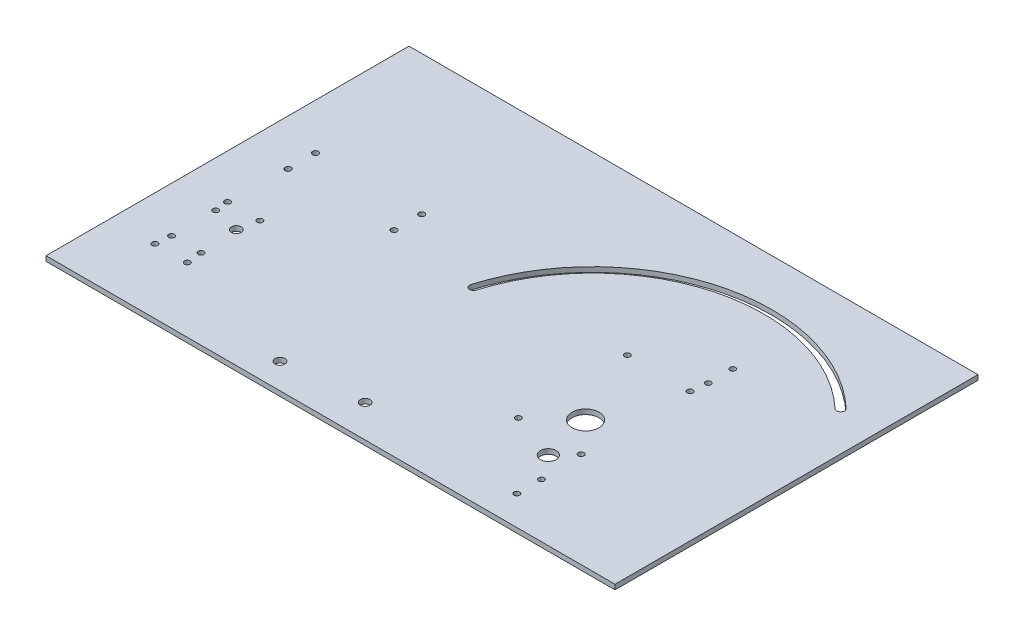
SolidWorks part; units mm, degrees
ref_plane "Front Plane" through (0, 0, 0) normal (0, 0, 1) x (1, 0, 0)
ref_plane "Top Plane" through (0, 0, 0) normal (0, 1, 0) x (1, 0, 0)
ref_plane "Right Plane" through (0, 0, 0) normal (1, 0, 0) x (0, 0, -1)
sketch "Sketch1" plane through (0, 0, 0) normal (0, 1, 0) x (1, 0, 0)
  line L1 (-158.75, 88.9) -> (158.75, 88.9)
  line L2 (-158.75, 88.9) -> (-158.75, -88.9)
  line L3 (-158.75, -88.9) -> (158.75, -88.9)
  line L4 (158.75, 88.9) -> (158.75, -88.9)
  line L5 (-158.75, 88.9) -> (158.75, -88.9) construction
  line L6 (-158.75, -88.9) -> (158.75, 88.9) construction
  circle A0 centre (-111.76, -12.7) radius 3.175
  circle A1 centre (107.95, -6.35) radius 8.7313
  circle A4 centre (-129.032, 55.88) radius 1.905
  circle A5 centre (-60.452, 55.88) radius 1.905
  circle A7 centre (-129.032, 38.1) radius 1.905
  circle A8 centre (-60.452, 38.1) radius 1.905
  point P0 (0, 0)
  dimension "D3" = 6.35
  dimension "D4" = 17.4625
  dimension "D14" = 3.81
  dimension "D17" = 17.78
  dimension "D1" = 317.5
  dimension "D2" = 177.8
  dimension "D5" = 46.99
  dimension "D6" = 266.7
  dimension "D7" = 95.25
  dimension "D8" = 76.2
  dimension "D13" = 29.718
  dimension "D15" = 68.58
  dimension "D16" = 127
extrude "Boss-Extrude1" add sketch "Sketch1" along normal blind 3.175
sketch "Sketch2" plane through (0, 3.175, 0) normal (0, 1, 0) x (1, 0, 0)
  line L0 (-158.75, 88.9) -> (-158.75, -88.9) construction
  line L1 (-158.75, -88.9) -> (158.75, -88.9) construction
  circle A0 centre (-89.0817, -33.177) radius 1.905
  circle A1 centre (-132.1376, -36.4483) radius 1.905
  dimension "D1" = 3.81
  dimension "D2" = 69.6683
  dimension "D3" = 52.4517
  dimension "D4" = 55.723
  dimension "D5" = 43.18
extrude "Cut-Extrude1" [suppressed] cut sketch "Sketch2" against normal through all
sketch "Sketch3" plane through (0, 0, 0) normal (0, -1, 0) x (-1, 0, 0)
  line L0 (158.75, -88.9) -> (-158.75, -88.9) construction
  line L1 (158.75, 88.9) -> (158.75, -88.9) construction
  circle A0 centre (23.8295, -72.39) radius 3.175
  circle A1 centre (-26.7643, -67.818) radius 3.175
  dimension "D1" = 6.35
  dimension "D2" = 4.572
  dimension "D3" = 16.51
  dimension "D4" = 185.5143
  dimension "D5" = 50.8
extrude "Cut-Extrude2" cut sketch "Sketch3" against normal through all
sketch "Sketch4" plane through (0, 3.175, 0) normal (0, 1, 0) x (1, 0, 0)
  line L0 (-158.75, -88.9) -> (158.75, -88.9) construction
  line L1 (158.75, 88.9) -> (133.35, 88.9)
  line L2 (158.75, 88.9) -> (158.75, -88.9)
  line L3 (158.75, -88.9) -> (133.35, -88.9)
  line L4 (133.35, 88.9) -> (133.35, -88.9)
  dimension "D1" = 25.4
extrude "Cut-Extrude3" cut sketch "Sketch4" against normal through all
sketch "Sketch5" plane through (0, 3.175, 0) normal (0, 1, 0) x (1, 0, 0)
  line L0 (133.35, 88.9) -> (-158.75, 88.9) construction
  line L1 (133.35, 88.9) -> (133.35, -88.9) construction
  circle A0 centre (115.57, -38.1) radius 5.08
  dimension "D3" = 10.16
  dimension "D1" = 127
  dimension "D2" = 17.78
extrude "Cut-Extrude4" cut sketch "Sketch5" against normal through all
sketch "Sketch6" plane through (0, 0, 0) normal (0, -1, 0) x (1, 0, 0)
  line L0 (-158.75, 88.9) -> (133.35, 88.9) construction
  line L1 (133.35, -88.9) -> (133.35, 88.9) construction
  line L2 (133.35, -88.9) -> (-158.75, -88.9) construction
  circle A0 centre (127, 69.85) radius 1.8034
  circle A2 centre (127, 53.975) radius 1.8034
  circle A3 centre (127, -53.975) radius 1.8034
  circle A4 centre (127, -69.85) radius 1.8034
  dimension "D4" = 3.6068
  dimension "D5" = 6.35
  dimension "D1" = 15.875
  dimension "D2" = 19.05
  dimension "D3" = 6.35
  dimension "D6" = 15.875
  dimension "D7" = 19.05
extrude "Cut-Extrude5" cut sketch "Sketch6" against normal through all
sketch "Sketch7" plane through (0, 3.175, 0) normal (0, 1, 0) x (1, 0, 0)
  line L0 (133.35, 88.9) -> (133.35, -88.9) construction
  line L1 (133.35, 88.9) -> (-158.75, 88.9) construction
  line L2 (-158.75, 88.9) -> (-158.75, -88.9) construction
  line L3 (-158.75, -88.9) -> (133.35, -88.9) construction
  circle A1 centre (125.73, 43.4975) radius 1.8415
  circle A2 centre (85.09, 43.4975) radius 1.8415
  circle A3 centre (85.09, -26.9875) radius 1.8415
  circle A4 centre (125.73, -26.9875) radius 1.8415
  circle A5 centre (-130.175, -46.99) radius 1.8415
  circle A6 centre (-109.22, -46.99) radius 1.8415
  circle A7 centre (-129.2225, -37.1475) radius 1.8415
  circle A8 centre (-110.1725, -37.1475) radius 1.8415
  circle A9 centre (-129.2225, -8.5725) radius 1.8415
  circle A10 centre (-130.175, 0) radius 1.8415
  circle A11 centre (-109.22, 0) radius 1.8415
  dimension "D1" = 7.62
  dimension "D5" = 3.683
  dimension "D10" = 3.683
  dimension "D15" = 3.683
  dimension "D2" = 40.64
  dimension "D3" = 70.485
  dimension "D4" = 61.9125
  dimension "D6" = 28.575
  dimension "D7" = 20.955
  dimension "D8" = 0.9525
  dimension "D9" = 19.05
  dimension "D11" = 88.9
  dimension "D12" = 8.5725
  dimension "D13" = 28.575
  dimension "D14" = 9.8425
extrude "Cut-Extrude6" cut sketch "Sketch7" against normal through all
sketch "Sketch8" plane through (0, 0, 0) normal (0, -1, 0) x (1, 0, 0)
  line L1 (-158.75, -88.9) -> (-158.75, 88.9) construction
  line L2 (-158.75, 88.9) -> (133.35, 88.9) construction
  line L3 (133.35, 88.9) -> (133.35, -88.9)
  line L4 (133.35, -88.9) -> (-158.75, -88.9) construction
  line L5 (133.35, -88.9) -> (-158.75, -88.9)
  line L6 (-158.75, -88.9) -> (-158.75, -146.05)
  line L7 (-158.75, -146.05) -> (209.55, -146.05)
  line L8 (209.55, -146.05) -> (209.55, 88.9)
  line L9 (209.55, 88.9) -> (133.35, 88.9)
  line L12 (133.35, -88.9) -> (133.35, 88.9) construction
  point P0 (209.55, -145.2409)
  point P13 (242.7872, -146.05)
  point P14 (142.6136, 96.8322)
  point P15 (-158.75, -88.9)
  point P16 (147.1467, 88.9)
  point P17 (133.35, -88.9)
  dimension "D1" = 76.2
  dimension "D2" = 57.15
extrude "Boss-Extrude2" add sketch "Sketch8" against normal through all
sketch "Sketch9" plane through (0, 0, 0) normal (0, -1, 0) x (1, 0, 0)
  line L0 (209.55, -146.05) -> (209.55, 88.9) construction
  line L1 (-158.75, 88.9) -> (209.55, 88.9) construction
  arc A0 (185.8872, -84.403) -> (182.4128, -80.697) centre (184.15, -82.55) ccw
  arc A1 (-0.1844, -31.0322) -> (-5.0573, -32.4678) centre (-2.6208, -31.75) ccw
  circle A2 centre (106.4105, 0.3734) radius 113.665 construction
  arc A3 (182.4128, -80.697) -> (-0.1844, -31.0322) centre (106.4105, 0.3734) cw
  arc A4 (185.8872, -84.403) -> (-5.0573, -32.4678) centre (106.4105, 0.3734) cw
  arc A5 (-5.0573, -32.4678) -> (-1.8758, -34.1783) centre (-2.6208, -31.75) ccw construction
  arc A6 (-1.8758, -34.1783) -> (-0.1844, -31.0322) centre (-2.6208, -31.75) ccw construction
  arc A7 (182.2777, -84.2664) -> (185.8872, -84.403) centre (184.15, -82.55) ccw construction
  arc A8 (182.4128, -80.697) -> (182.2777, -84.2664) centre (184.15, -82.55) ccw construction
  point P16 (184.4553, -80.0284)
  dimension "D1" = 5.08
  dimension "D6" = 227.33
  dimension "D2" = 25.4
  dimension "D3" = 171.45
  dimension "D4" = 120.65
  dimension "D5" = 186.7708
extrude "Cut-Extrude7" cut sketch "Sketch9" against normal through all
